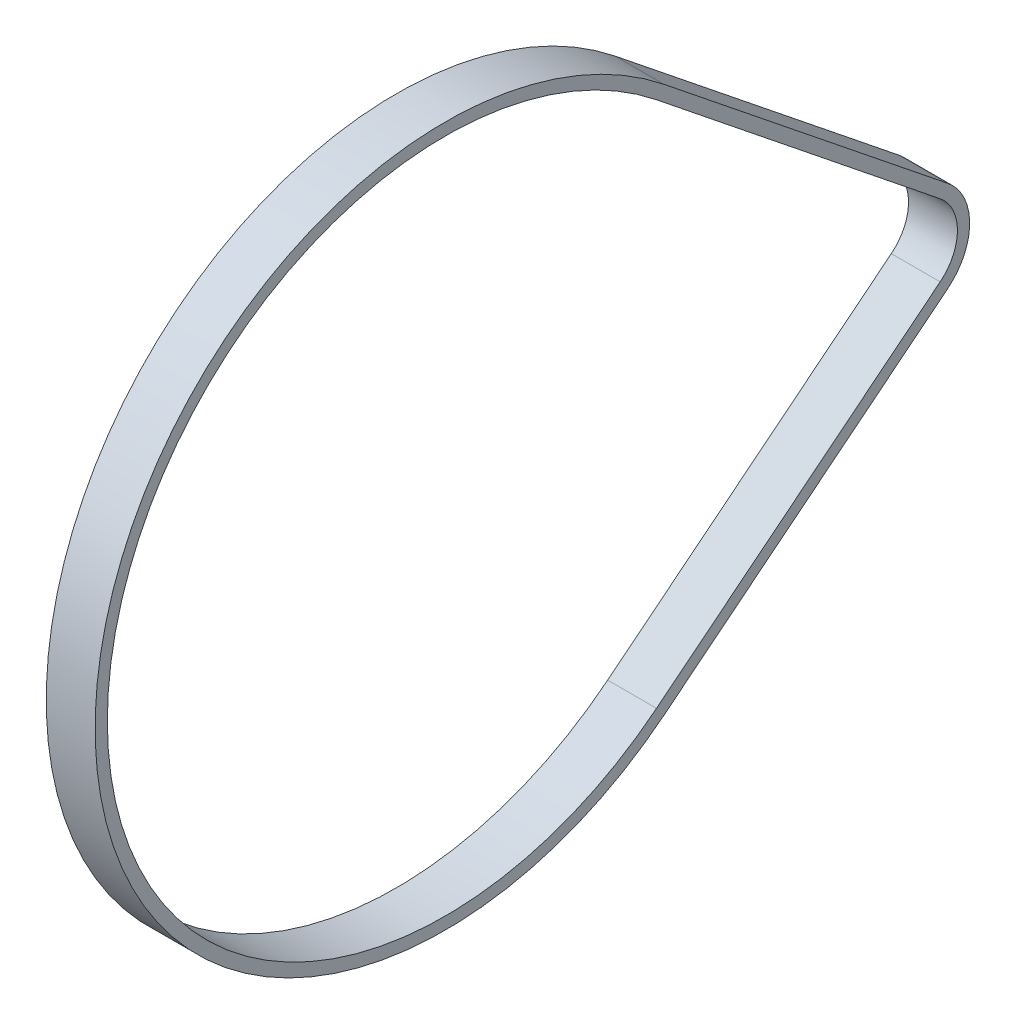
SolidWorks part; units mm, degrees
ref_plane "Front Plane" through (0, 0, 0) normal (0, 0, 1) x (1, 0, 0)
ref_plane "Top Plane" through (0, 0, 0) normal (0, 1, 0) x (1, 0, 0)
ref_plane "Right Plane" through (0, 0, 0) normal (1, 0, 0) x (0, 0, -1)
sketch "Sketch1" plane through (0, 0, 0) normal (1, 0, 0) x (0, 0, -1)
  line L0 (0, 37.672) -> (0, -29.9312) construction
  line L1 (-68.1193, 0) -> (49.7993, 0) construction
  line L2 (-2.8747, 55.8657) -> (55.1592, 9.3109)
  line L3 (-2.8747, -55.8657) -> (55.1592, -9.3109)
  line L4 (-47.69, 71.6197) -> (-47.69, 0) construction
  line L5 (-47.69, 0) -> (-50.6891, 71.5569) construction
  line L6 (47.69, 0) -> (59.2516, 2.9685) construction
  line L9 (-4.439, 53.9156) -> (53.5949, 7.3609)
  line L10 (-4.439, -53.9156) -> (53.5949, -7.3609)
  arc A0 (-2.8747, 55.8657) -> (-2.8747, -55.8657) centre (-47.69, 0) ccw
  arc A1 (55.1592, -9.3109) -> (55.1592, 9.3109) centre (47.69, 0) ccw
  arc A4 (53.5949, -7.3609) -> (53.5949, 7.3609) centre (47.69, 0) ccw
  arc A5 (-4.439, 53.9156) -> (-4.439, -53.9156) centre (-47.69, 0) ccw
  point P6 (-47.69, -71.6197)
  point P14 (-47.69, 69.1197)
  point P22 (-47.69, -69.1197)
  dimension "D4" = 71.6197
  dimension "D5" = 11.9366
  dimension "D1" = 2.4
  dimension "D2" = 14.4
  dimension "D6" = 95.38
  dimension "D8" = 143.2394
  dimension "D9" = 138.2394
  dimension "D7" = 2.5
extrude "Boss-Extrude1" add sketch "Sketch1" along normal mid plane 10
equation "\"D1@Sketch1\"=360/\"LARGE_TEETH\""
equation "\"D2@Sketch1\"=360/\"SMALL_TEETH\""
equation "\"LARGE_TEETH\" = 150"
equation "\"SMALL_TEETH\" = 25"
equation "\"BELT_LENGTH\" = 492mm"
equation "\"PITCH\" = 3mm"
equation "\"LARGE_C\"= \"LARGE_TEETH\" * \"PITCH\""
equation "\"SMALL_C\"= \"SMALL_TEETH\" * \"PITCH\""
equation "\"LARGE_RADIUS\"= \"LARGE_C\" / ( 2 * PI )"
equation "\"SMALL_RADIUS\"= \"SMALL_C\" / ( 2 * PI )"
equation "\"D4@Sketch1\"=\"LARGE_RADIUS\""
equation "\"D5@Sketch1\"=\"SMALL_RADIUS\""
equation "\"D3@Sketch1\"=\"BELT_LENGTH\""
